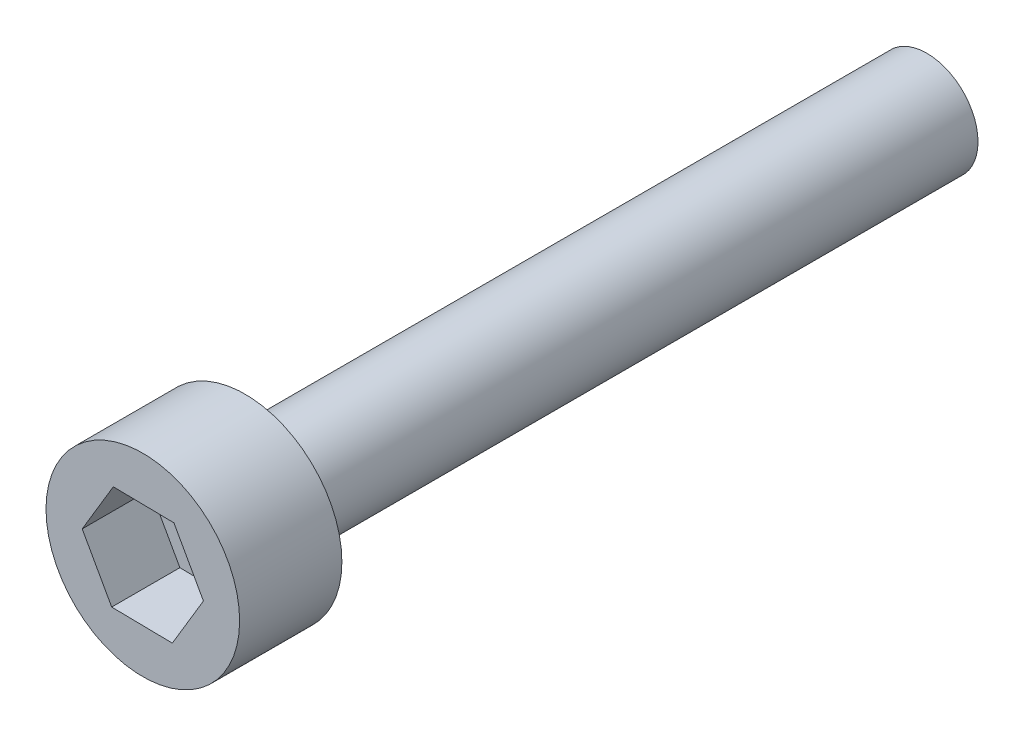
SolidWorks part; units mm, degrees
material "AISI 304"
ref_plane "前视基准面" through (0, 0, 0) normal (0, 0, 1) x (1, 0, 0)
ref_plane "上视基准面" through (0, 0, 0) normal (0, 1, 0) x (1, 0, 0)
ref_plane "右视基准面" through (0, 0, 0) normal (1, 0, 0) x (0, 0, -1)
sketch "草图1" plane through (0, 0, 0) normal (0, 0, 1) x (1, 0, 0)
  circle A0 centre (0, 0) radius 2.84
  dimension "D1" = 5.68
extrude "凸台-拉伸1" add sketch "草图1" along normal blind 3
sketch "草图2" plane through (0, 0, 0) normal (0, 0, -1) x (-1, 0, 0)
  circle A0 centre (0, 0) radius 1.5
  dimension "D1" = 3
extrude "凸台-拉伸2" add sketch "草图2" along normal blind 20
cosmetic thread "装饰螺纹线1" parameters "D2"=2
sketch "草图3" plane through (0, 0, 3) normal (0, 0, 1) x (1, 0, 0)
  line L1 (0.9126, 1.5262) -> (-0.8654, 1.5534)
  line L2 (-0.8654, 1.5534) -> (-1.778, 0.0272)
  line L3 (-1.778, 0.0272) -> (-0.9126, -1.5262)
  line L4 (-0.9126, -1.5262) -> (0.8654, -1.5534)
  line L5 (0.8654, -1.5534) -> (1.778, -0.0272)
  line L6 (1.778, -0.0272) -> (0.9126, 1.5262)
  circle A0 centre (0, 0) radius 1.54 construction
  dimension "D1" = 3.08
extrude "切除-拉伸1" cut sketch "草图3" against normal blind 2
